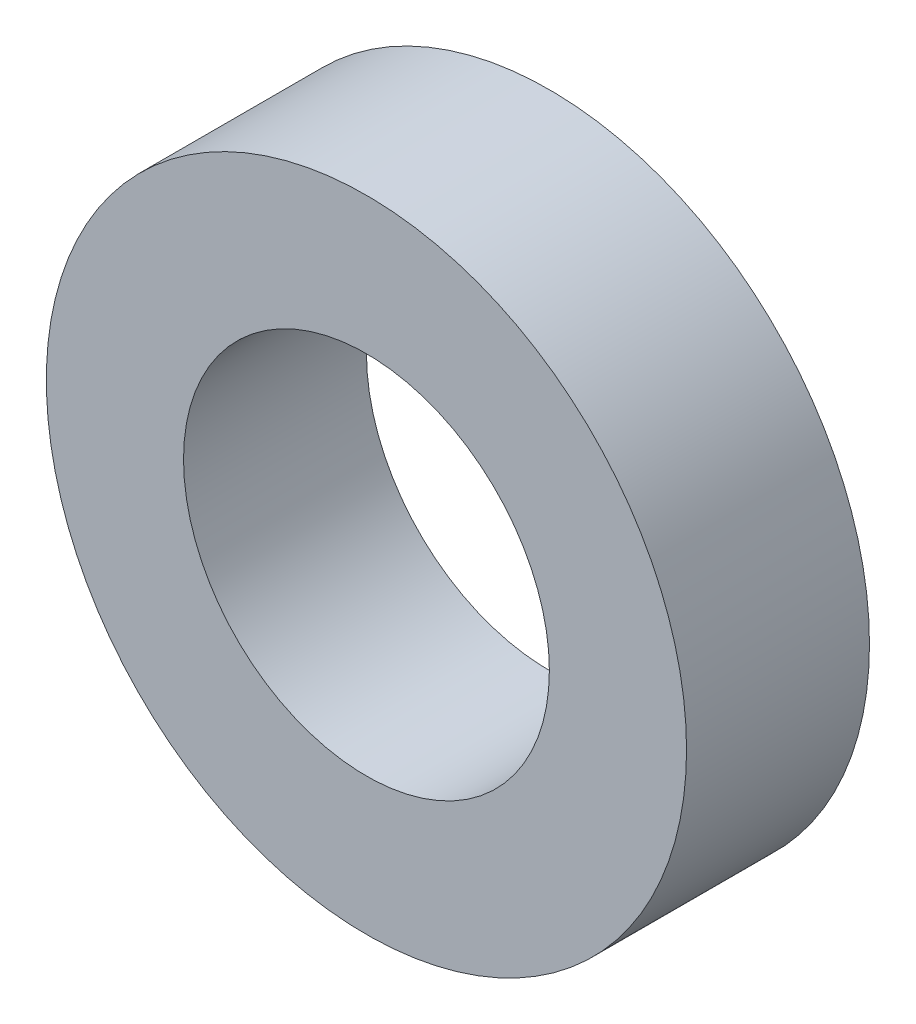
SolidWorks part; units mm, degrees
ref_plane "前视基准面" through (0, 0, 0) normal (0, 0, 1) x (1, 0, 0)
ref_plane "上视基准面" through (0, 0, 0) normal (0, 1, 0) x (1, 0, 0)
ref_plane "右视基准面" through (0, 0, 0) normal (1, 0, 0) x (0, 0, -1)
sketch "草图1" plane through (0, 0, 0) normal (0, 0, 1) x (1, 0, 0)
  circle A0 centre (0, 0) radius 10
  circle A1 centre (0, 0) radius 17.5
extrude "凸台-拉伸1" add sketch "草图1" along normal blind 10
